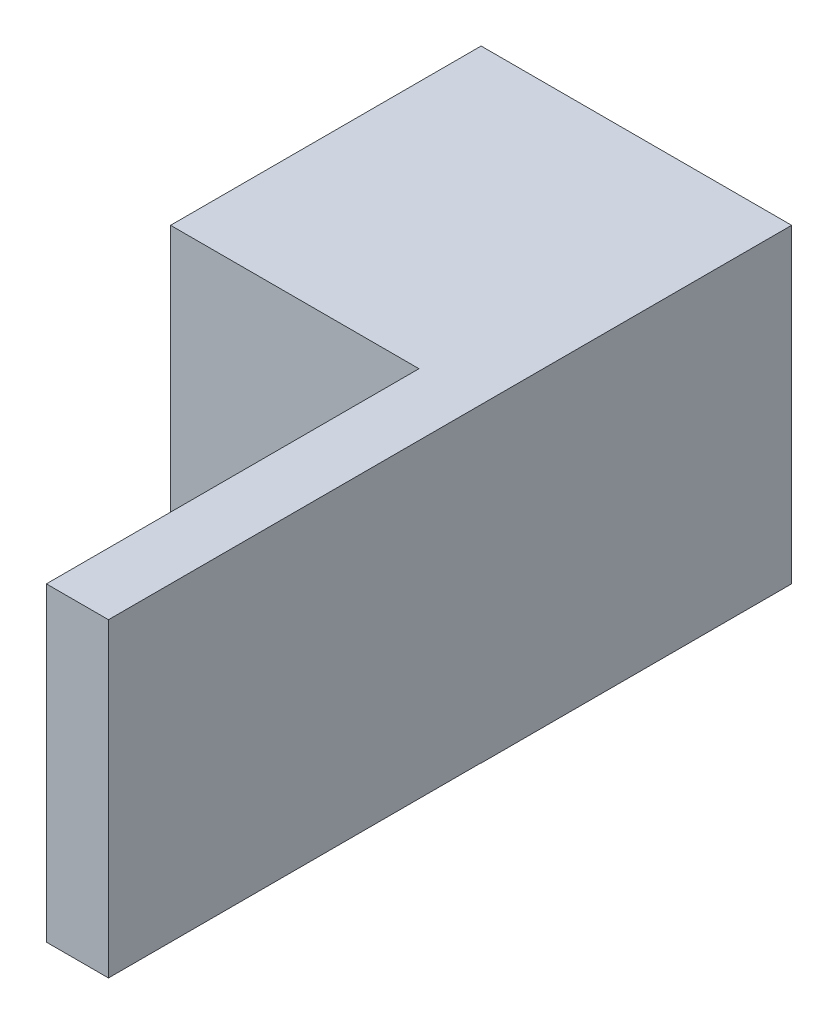
SolidWorks part; units mm, degrees
ref_plane "Front Plane" through (0, 0, 0) normal (0, 0, 1) x (1, 0, 0)
ref_plane "Top Plane" through (0, 0, 0) normal (0, 1, 0) x (1, 0, 0)
ref_plane "Right Plane" through (0, 0, 0) normal (1, 0, 0) x (0, 0, -1)
sketch "Sketch1" plane through (0, 0, 0) normal (0, 0, 1) x (1, 0, 0)
  line L2 (42.2648, -500) -> (-457.7352, -500)
  line L3 (42.2648, -500) -> (42.2648, 0)
  line L4 (42.2648, 0) -> (-457.7352, 0)
  line L5 (-457.7352, -500) -> (-457.7352, 0)
  dimension "D1" = 500
  dimension "D2" = 500
extrude "Boss-Extrude1" add sketch "Sketch1" along normal blind 500
sketch "Sketch2" plane through (0, 0, 0) normal (0, 0, -1) x (-1, 0, 0)
  line L1 (-42.2648, 0) -> (57.7352, 0)
  line L2 (-42.2648, 0) -> (-42.2648, -499.6168)
  line L3 (-42.2648, -499.6168) -> (57.7352, -499.6168)
  line L4 (57.7352, 0) -> (57.7352, -499.6168)
  dimension "D1" = 100
extrude "Boss-Extrude2" add sketch "Sketch2" against normal blind 1100
